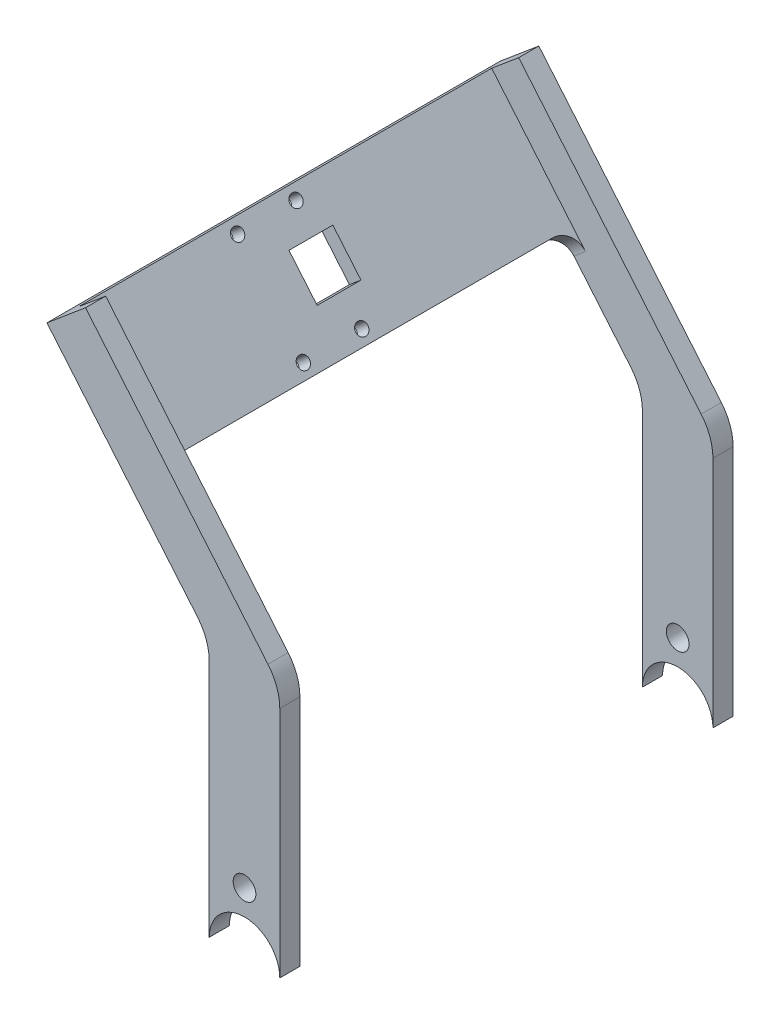
SolidWorks part; units mm, degrees
ref_plane "Piano frontale" through (0, 0, 0) normal (0, 0, 1) x (1, 0, 0)
ref_plane "Piano superiore" through (0, 0, 0) normal (0, 1, 0) x (1, 0, 0)
ref_plane "Piano destro" through (0, 0, 0) normal (1, 0, 0) x (0, 0, -1)
sketch "Schizzo1" plane through (0, 0, 0) normal (0, 0, 1) x (1, 0, 0)
  line L9 (-7, 0) -> (-7, 51.1273)
  line L10 (-7, 51.1273) -> (-39.2277, 89.5348)
  line L11 (-39.2277, 89.5348) -> (-31.5673, 95.9627)
  line L12 (-31.5673, 95.9627) -> (7, 50)
  line L13 (7, 50) -> (7, 0)
  line L14 (0, 58.3423) -> (0, 0) construction
  line L16 (-7, 50) -> (7, 50) construction
  line L17 (-7, 0) -> (7, 0) construction
  arc A1 (7, 0) -> (-7, 0) centre (0, 0) ccw
  circle A2 centre (0, 12) radius 2.25 construction
  dimension "D3" = 4.5
  dimension "D1" = 14
  dimension "D2" = 12
  dimension "D9" = 10
  dimension "D10" = 40
  dimension "D11" = 60
  dimension "D12" = 50
extrude "Estrusione-Estrusione1" add sketch "Schizzo1" along normal blind 4
sketch "Schizzo2" plane through (0, 0, 4) normal (0, 0, 1) x (1, 0, 0)
  line L2 (-7, 51.1273) -> (-7, 0) construction
  point P0 (0, 12)
  dimension "D1" = 7
  dimension "D2" = 12
sketch "Schizzo4" plane through (0, 0, 0) normal (0, 0, 1) x (1, 0, 0)
  line L5 (-39.2277, 89.5348) -> (-23.158, 70.3837)
  line L6 (-39.2277, 89.5348) -> (-7, 51.1273) construction
  line L7 (-23.158, 70.3837) -> (-20.8599, 72.312)
  line L8 (-20.8599, 72.312) -> (-36.9296, 91.4632)
  line L9 (-31.5673, 95.9627) -> (-39.2277, 89.5348) construction
  line L10 (-36.9296, 91.4632) -> (-39.2277, 89.5348)
  dimension "D3" = 25
  dimension "D4" = 3
extrude "Estrusione-Estrusione2" add sketch "Schizzo4" against normal blind 82
sketch "Schizzo5" plane through (0, 0, -82) normal (0, 0, -1) x (-1, 0, 0)
  line L13 (-7, 0) -> (-7, 50)
  line L14 (-7, 50) -> (31.5673, 95.9627)
  line L15 (31.5673, 95.9627) -> (39.2277, 89.5348)
  line L16 (39.2277, 89.5348) -> (7, 51.1273)
  line L17 (7, 51.1273) -> (7, 0)
  line L18 (-7, 0) -> (7, 0) construction
  arc A0 (7, 0) -> (-7, 0) centre (0, 0) ccw construction
  arc A1 (7, 0) -> (-7, 0) centre (0, 0) ccw
extrude "Estrusione-Estrusione3" add sketch "Schizzo5" along normal blind 4
hole_wizard "Foro per Vite M4-1" positions "Schizzo2" profile "Schizzo3" hole size "M4" standard "ISO"
sketch "Schizzo3" plane through (0, 12, 4) normal (1, 0, 0) x (0, -1, 0)
  line L0 (0, 0) -> (0, 189.3519)
  line L1 (0, 189.3519) -> (2.25, 188)
  line L2 (2.25, 188) -> (2.25, 0)
  line L5 (2.25, 0) -> (0, 0)
  line L10 (0, 189.3519) -> (-2.25, 188) construction
  line L11 (0, -6.35) -> (0, 107.95) construction
  dimension "Hole Dia." = 4.5
  dimension "Hole Depth" = 188
  dimension "Drill Angle" = 118
sketch "Schizzo6" plane through (23.3657, 19.6061, 0) normal (0.766, 0.6428, 0) x (0, 0, -1)
  line L0 (30.05, 91.4527) -> (41.65, 91.4527) construction
  line L1 (36.65, 85.8527) -> (45.35, 85.8527)
  line L2 (36.65, 85.8527) -> (36.65, 77.1527)
  line L3 (36.65, 77.1527) -> (45.35, 77.1527)
  line L4 (45.35, 85.8527) -> (45.35, 77.1527)
  line L5 (30.05, 71.1527) -> (30.05, 91.4527) construction
  line L6 (30.05, 71.1527) -> (41.65, 71.1527) construction
  line L7 (41.65, 71.1527) -> (41.65, 91.4527) construction
  line L8 (30.05, 81.3027) -> (0, 81.3027) construction
  line L9 (0, 33.8027) -> (0, 93.8027) construction
  line L10 (0, 68.8027) -> (0, 93.8027) construction
  line L11 (36.65, 85.8527) -> (45.35, 77.1527) construction
  line L12 (36.65, 77.1527) -> (45.35, 85.8527) construction
  circle A0 centre (30.05, 91.4527) radius 1.2
  circle A1 centre (41.65, 91.4527) radius 1.2
  circle A2 centre (30.05, 71.1527) radius 1.2
  circle A3 centre (41.65, 71.1527) radius 1.2
  point P18 (0, 81.3027)
  point P19 (41, 81.5027)
  dimension "D1" = 2.4
  dimension "D2" = 20.3
  dimension "D3" = 11.6
  dimension "D4" = 8.7
  dimension "D5" = 5
  dimension "D6" = 6
  dimension "D7" = 41
extrude "Taglio-Estrusione1" cut sketch "Schizzo6" against normal blind 10
fillet "Raccordo1" radius 10 4 edges at (-7, 51.1273, 2) (-7, 51.1273, -84) (7, 50, 2) (7, 50, -84)
fillet "Raccordo2" radius 4 2 edges at (-22.0089, 71.3479, 0) (-22.0089, 71.3479, -82)
